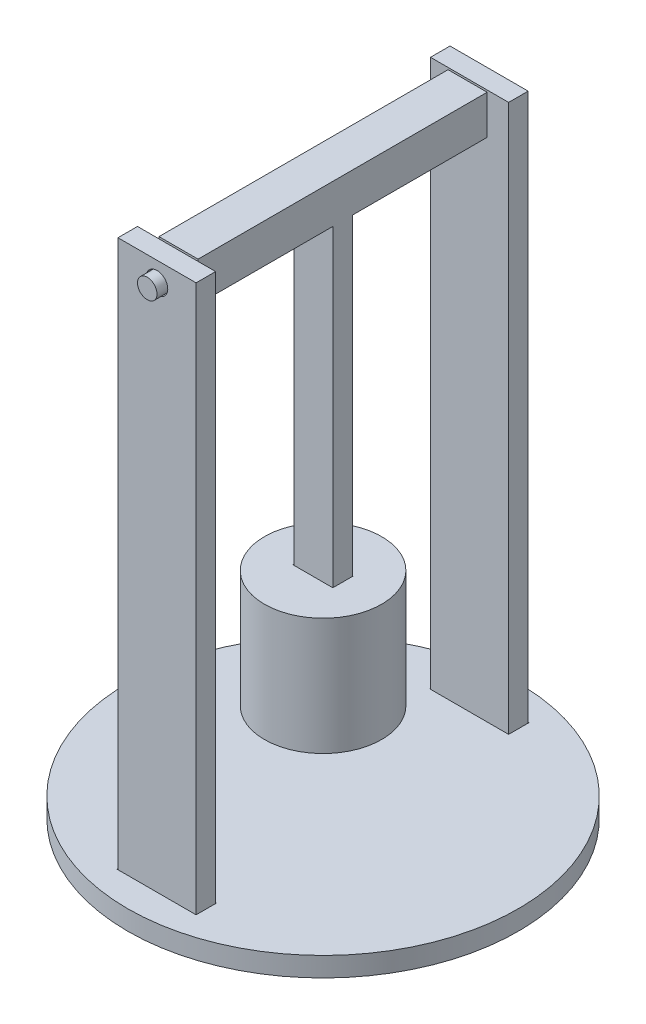
SolidWorks part; units mm, degrees
other "Base plate"
other "Axle"
other "Pendulum arm"
other "Stand side"
other "Weight"
ref_plane "Front Plane" through (0, 0, 0) normal (0, 0, 1) x (1, 0, 0)
ref_plane "Top Plane" through (0, 0, 0) normal (0, 1, 0) x (1, 0, 0)
ref_plane "Right Plane" through (0, 0, 0) normal (1, 0, 0) x (0, 0, -1)
other "Center of Mass"
sketch "Sketch1" plane through (0, 0, 0) normal (0, 1, 0) x (1, 0, 0)
  line L0 (0, -40) -> (0, 40) construction
  line L1 (-55, 0) -> (55, 0) construction
  line L2 (-10.1, 42.6) -> (10.1, 42.6)
  line L3 (-10.1, 42.6) -> (-10.1, 37.4)
  line L4 (-10.1, 37.4) -> (10.1, 37.4)
  line L5 (10.1, 42.6) -> (10.1, 37.4)
  line L6 (-10.1, -37.4) -> (10.1, -37.4)
  line L7 (10.1, -42.6) -> (10.1, -37.4)
  line L8 (-10.1, -42.6) -> (10.1, -42.6)
  line L9 (-10.1, -42.6) -> (-10.1, -37.4)
  circle A0 centre (0, 0) radius 50
  point P7 (0, 0)
  point P10 (0, 42.6)
  point P11 (-10.1, 40)
  dimension "D2" = 5.2
  dimension "D3" = 100
  dimension "D1" = 80
  dimension "D4" = 20.2
extrude "Boss-Extrude1" add sketch "Sketch1" along normal blind 5
sketch "Sketch2" plane through (0, 0, 0) normal (0, -1, 0) x (1, 0, 0)
  line L1 (-10, 42.5) -> (10, 42.5)
  line L2 (-10, 42.5) -> (-10, 37.5)
  line L3 (-10, 37.5) -> (10, 37.5)
  line L4 (10, 42.5) -> (10, 37.5)
  line L5 (10.1, 42.6) -> (10.1, 37.4) construction
  line L6 (10.1, 37.4) -> (-10.1, 37.4) construction
  line L7 (55, 0) -> (-55, 0) construction
  line L8 (10, -42.5) -> (10, -37.5)
  line L9 (-10, -37.5) -> (10, -37.5)
  line L10 (-10, -42.5) -> (-10, -37.5)
  line L11 (-10, -42.5) -> (10, -42.5)
  point P4 (10, 40)
  point P5 (0, 37.5)
  point P8 (10.1, 40)
  point P11 (0, 37.4)
  point P18 (0, -37.5)
  point P19 (10, -40)
  dimension "D1" = 20
  dimension "D2" = 5
extrude "Boss-Extrude2" add sketch "Sketch2" against normal blind 145 separate body
sketch "Sketch3" plane through (0, 0, 0) normal (0, 0, 1) x (1, 0, 0)
  line L0 (10, 145) -> (-10, 145) construction
  circle A0 centre (0, 140) radius 2.75
  dimension "D1" = 5.5
  dimension "D2" = 5
extrude "Cut-Extrude1" cut sketch "Sketch3" against normal through all both and the other way through all
sketch "Sketch4" plane through (0, 0, 0) normal (0, 0, 1) x (1, 0, 0)
  circle A0 centre (0, 140) radius 2.5
  dimension "D1" = 5
extrude "Boss-Extrude3" add sketch "Sketch4" along normal mid plane 90 separate body
sketch "Sketch5" plane through (0, 0, 0) normal (0, 0, 1) x (1, 0, 0)
  line L1 (-5, 135) -> (5, 135)
  line L2 (-5, 135) -> (-5, 145)
  line L3 (-5, 145) -> (5, 145)
  line L4 (5, 135) -> (5, 145)
  line L5 (-5, 135) -> (5, 145) construction
  line L6 (-5, 145) -> (5, 135) construction
  circle A0 centre (0, 140) radius 2.5
  circle A3 centre (0, 140) radius 2.5 construction
  point P5 (0, 140)
  dimension "D1" = 10
extrude "Boss-Extrude4" add sketch "Sketch5" along normal mid plane 74 separate body
sketch "Sketch10" plane through (0, 0, 0) normal (0, 0, 1) x (1, 0, 0)
  line L1 (-5, 135) -> (5, 135)
  line L2 (-5, 135) -> (-5, 25)
  line L3 (-5, 25) -> (5, 25)
  line L4 (5, 135) -> (5, 25)
  dimension "D1" = 115
extrude "Boss-Extrude7" add sketch "Sketch10" along normal mid plane 5
ref_plane "Plane3" through (0, 140, 0) normal (0, 1, 0) x (1, 0, 0)
ref_plane "Plane4" through (0, 40, 0) normal (0, 1, 0) x (1, 0, 0)
sketch "Sketch11" plane through (0, 40, 0) normal (0, 1, 0) x (1, 0, 0)
  line L0 (-2.5, 0) -> (2.5, 0) construction
  line L1 (-5.1, -2.6) -> (5.1, -2.6)
  line L2 (-5.1, -2.6) -> (-5.1, 2.6)
  line L3 (-5.1, 2.6) -> (5.1, 2.6)
  line L4 (5.1, -2.6) -> (5.1, 2.6)
  line L5 (-5.1, -2.6) -> (5.1, 2.6) construction
  line L6 (-5.1, 2.6) -> (5.1, -2.6) construction
  circle A0 centre (0, 0) radius 15
  point P0 (0, 0)
  dimension "D3" = 30
  dimension "D1" = 5.2
  dimension "D2" = 10.2
extrude "Boss-Extrude8" add sketch "Sketch11" along normal mid plane 30 separate body
sketch "Sketch15" plane through (0, 0, 0) normal (1, 0, 0) x (0, 0, -1)
  line L0 (0, 140) -> (0, 40)
  point P4 (0, 135)
  dimension "D1" = 100
  dimension "D2" = 95
